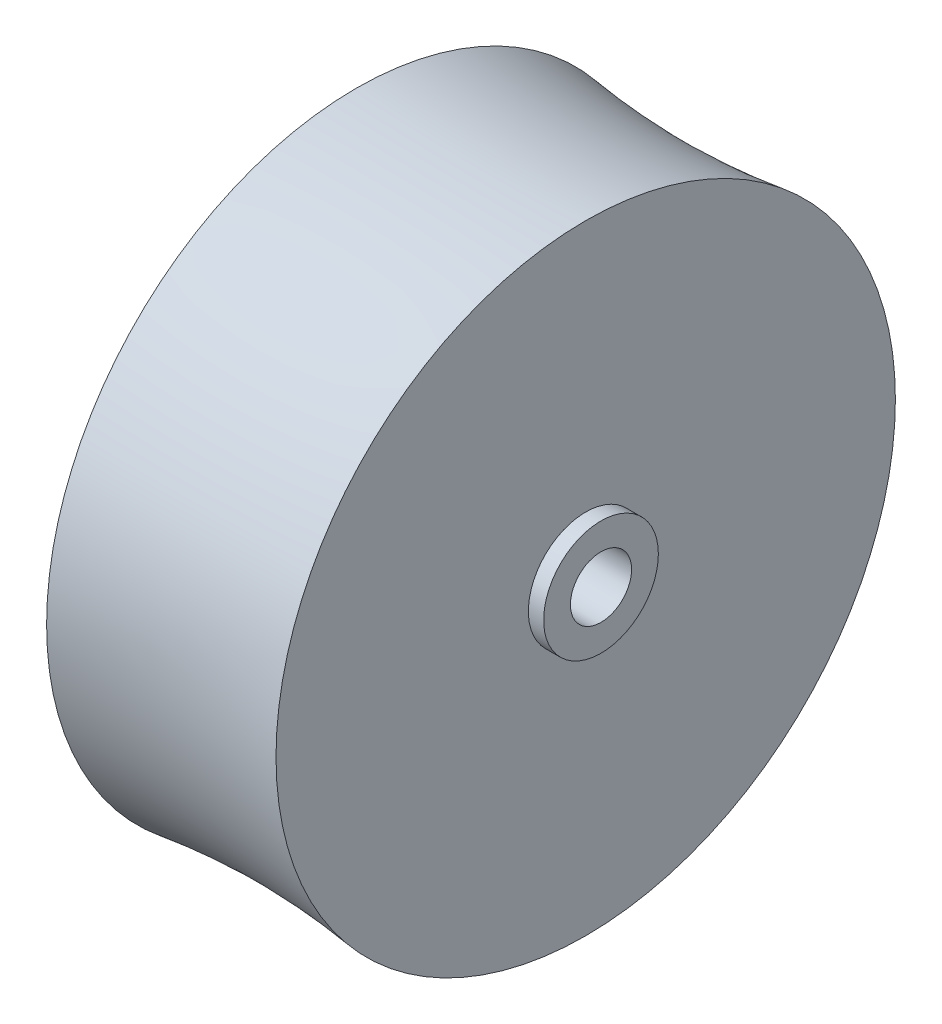
SolidWorks part; units mm, degrees
ref_plane "Front Plane" through (0, 0, 0) normal (0, 0, 1) x (1, 0, 0)
ref_plane "Top Plane" through (0, 0, 0) normal (0, 1, 0) x (1, 0, 0)
ref_plane "Right Plane" through (0, 0, 0) normal (1, 0, 0) x (0, 0, -1)
sketch "Sketch1" plane through (0, 0, 0) normal (0, 0, 1) x (1, 0, 0)
  line L0 (0, 0) -> (-55.291, 0) construction
  line L2 (-34, 0) -> (0, 0)
  line L3 (-34, 0) -> (-34, 40.5)
  line L4 (-34, 40.5) -> (0, 40.5)
  line L5 (0, 0) -> (0, 40.5)
  line L6 (-32, 40.5) -> (-34, 40.5)
  line L7 (-32, 40.5) -> (-32, 7.5)
  line L8 (-32, 7.5) -> (-34, 7.5)
  line L9 (-34, 40.5) -> (-34, 7.5)
  line L10 (-34, 4) -> (0, 4)
  line L11 (-34, 4) -> (-34, 0)
  line L12 (-34, 0) -> (0, 0)
  line L13 (0, 4) -> (0, 0)
  line L14 (-2, 40.5) -> (0, 40.5)
  line L15 (-2, 40.5) -> (-2, 7.5)
  line L16 (-2, 7.5) -> (0, 7.5)
  line L17 (0, 40.5) -> (0, 7.5)
  spline S0 degree 2 poles (-32, 40.5) (-17, 38.5) (-2, 40.5) knots 0 0 0 1 1 1
  point P15 (-17, 40.5)
  dimension "D1" = 34
  dimension "D2" = 40.5
  dimension "D3" = 2
  dimension "D4" = 2
  dimension "D5" = 39.5
  dimension "D6" = 4
  dimension "D7" = 3.5
revolve "Revolve1" add sketch "Sketch1" angle 360 about L0
